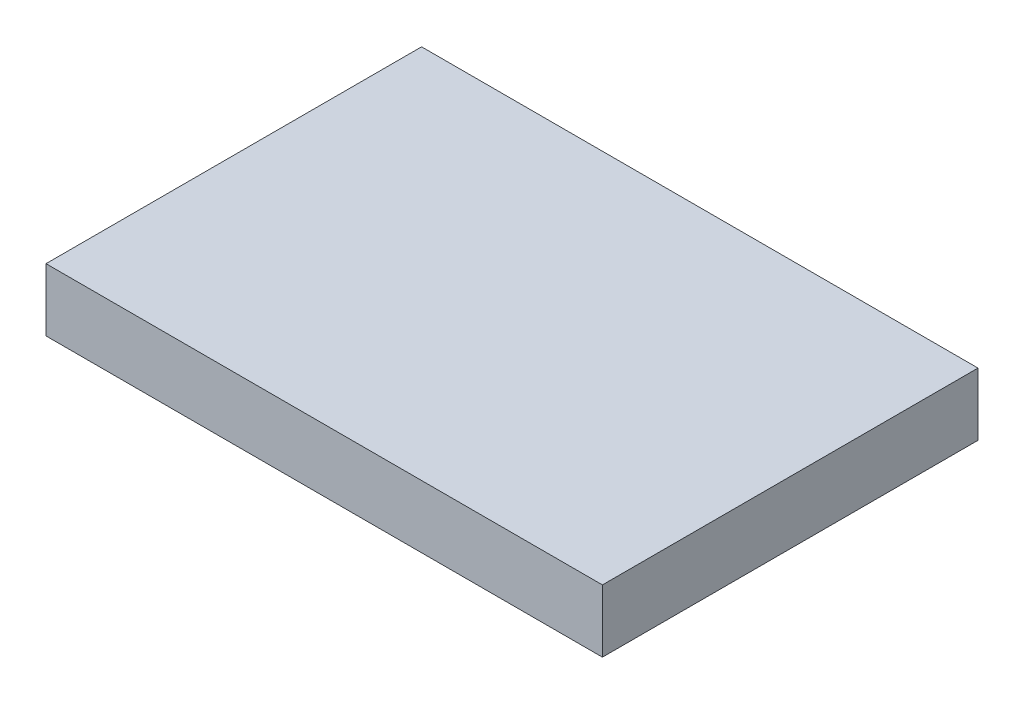
SolidWorks part; units mm, degrees
ref_plane "Front Plane" through (0, 0, 0) normal (0, 0, 1) x (1, 0, 0)
ref_plane "Top Plane" through (0, 0, 0) normal (0, 1, 0) x (1, 0, 0)
ref_plane "Right Plane" through (0, 0, 0) normal (1, 0, 0) x (0, 0, -1)
sketch "Sketch1" plane through (2.7259, 0, 0) normal (0, -1, 0) x (0, 0, -1)
  line L0 (-27, -2.7259) -> (27, -2.7259)
  line L2 (27, 37.2741) -> (27, -42.7259)
  line L4 (-27, 37.2741) -> (-27, -42.7259)
  line L5 (27, 37.2741) -> (-27, -42.7259) construction
  line L6 (27, -42.7259) -> (-27, 37.2741) construction
  line L7 (0.5, 37.2741) -> (0.5, -42.7259)
  line L8 (-27, 37.2741) -> (0.5, 37.2741)
  line L9 (0.5, 37.2741) -> (27, 37.2741)
  line L10 (-27, -42.7259) -> (0.5, -42.7259)
  line L11 (27, -42.7259) -> (0.5, -42.7259)
  line L12 (-13.25, 37.2741) -> (-13.25, -42.7259)
  line L13 (13.75, 37.2741) -> (13.75, -42.7259)
  point P0 (0, -2.7259)
  dimension "D1" = 80
  dimension "D2" = 54
  dimension "D3" = 13.75
extrude "Boss-Extrude1" add sketch "Sketch1" along normal blind 9 contours L8 L12 L0 L4 | L0 L12 L10 L4 | L12 L8 L7 L0 | L12 L0 L7 L10 | L9 L13 L0 L7 | L0 L13 L11 L7 | L13 L9 L2 L0 | L13 L0 L2 L11
sketch "Sketch7" plane through (0, -9, 0) normal (0, -1, 0) x (1, 0, 0)
  line L0 (-40, 27) -> (-40, -27) construction
  line L2 (-15, 4.9) -> (-31, 4.9)
  line L3 (-32, 0) -> (-16, 0)
  line L4 (-31, 4.9) -> (-31, 9.9)
  line L5 (-31, 9.9) -> (-15, 9.9)
  line L6 (-15, 9.9) -> (-15, 4.9)
  line L7 (-32, -4) -> (-32, 4) construction
  line L9 (-15, -9.9) -> (-15, -4.9)
  line L10 (-31, -9.9) -> (-15, -9.9)
  line L11 (-31, -4.9) -> (-31, -9.9)
  line L12 (-15, -4.9) -> (-31, -4.9)
  line L13 (0, 27) -> (0, -27)
  line L14 (40, 27) -> (-40, 27) construction
  line L15 (40, -27) -> (-40, -27) construction
  line L16 (15, -4.9) -> (31, -4.9)
  line L17 (31, -4.9) -> (31, -9.9)
  line L18 (31, -9.9) -> (15, -9.9)
  line L19 (15, -9.9) -> (15, -4.9)
  line L20 (15, 9.9) -> (15, 4.9)
  line L21 (31, 9.9) -> (15, 9.9)
  line L22 (31, 4.9) -> (31, 9.9)
  line L23 (32, 0) -> (16, 0)
  line L24 (15, 4.9) -> (31, 4.9)
  line L25 (3.5, 9.9) -> (-3.5, 9.9)
  line L26 (-3.5, 9.9) -> (-3.5, -10.1)
  line L30 (-3.5, -10.1) -> (0, -10.1)
  line L31 (3.5, -10.1) -> (0, -10.1)
  line L32 (3.5, 9.9) -> (3.5, -10.1)
  point P33 (-1.75, -10.1)
  point P37 (0, 9.9)
  dimension "D1" = 5
  dimension "D2" = 20
  dimension "D3" = 3.5
  dimension "D4" = 9.8
  dimension "D5" = 16
  dimension "D6" = 9
sketch "Sketch2" plane through (0, 0, 0) normal (0, 1, 0) x (1, 0, 0)
  line L0 (-40, 0) -> (40, 0)
  line L1 (-40, -27) -> (-40, 27) construction
  line L2 (40, -27) -> (40, 27) construction
sketch "Sketch3" plane through (0, -9, 0) normal (0, -1, 0) x (1, 0, 0)
  line L0 (-40, 0) -> (40, 0)
sketch "Sketch5" plane through (0, 0, 0) normal (0, 1, 0) x (1, 0, 0)
  line L0 (-40, 0) -> (40, 0) construction
  point P0 (0, 0)
sketch "Sketch6" plane through (0, -9, 0) normal (0, -1, 0) x (1, 0, 0)
  point P0 (0, 0)
